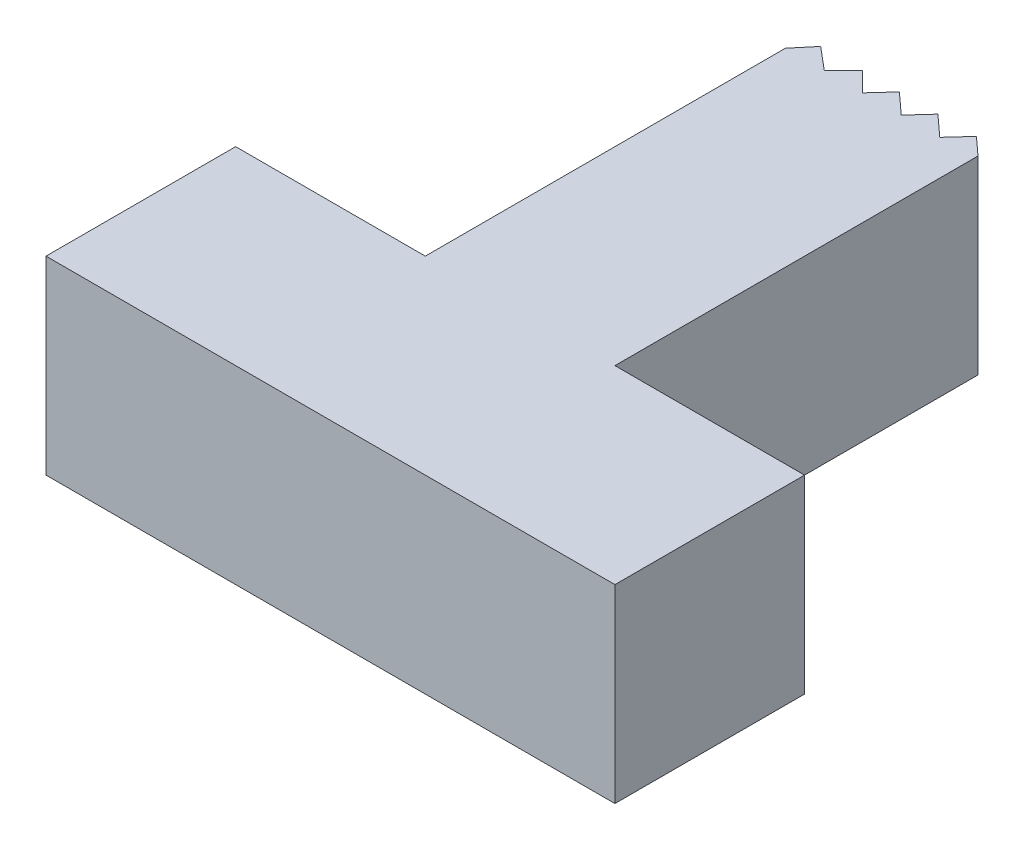
SolidWorks part; units mm, degrees
ref_plane "前视基准面" through (0, 0, 0) normal (0, 0, 1) x (1, 0, 0)
ref_plane "上视基准面" through (0, 0, 0) normal (0, 1, 0) x (1, 0, 0)
ref_plane "右视基准面" through (0, 0, 0) normal (1, 0, 0) x (0, 0, -1)
sketch "草图1" plane through (0, 0, 0) normal (0, 0, 1) x (1, 0, 0)
  line L1 (-3, 1) -> (3, 1)
  line L2 (-3, 1) -> (-3, -1)
  line L3 (-3, -1) -> (3, -1)
  line L4 (3, 1) -> (3, -1)
  line L5 (-3, 1) -> (3, -1) construction
  line L6 (-3, -1) -> (3, 1) construction
  point P0 (0, 0)
extrude "凸台-拉伸1" add sketch "草图1" along normal blind 2
sketch "草图2" plane through (0, 0, 0) normal (0, 0, -1) x (-1, 0, 0)
  line L0 (3, -1) -> (-3, -1) construction
  line L1 (-1, 1) -> (1, 1)
  line L2 (-1, 1) -> (-1, -1)
  line L3 (-1, -1) -> (1, -1)
  line L4 (1, 1) -> (1, -1)
  line L5 (-1, 1) -> (1, -1) construction
  line L6 (-1, -1) -> (1, 1) construction
  point P0 (0, 0)
extrude "凸台-拉伸2" add sketch "草图2" along normal blind 4
sketch "草图3" plane through (0, 1, 0) normal (0, 1, 0) x (1, 0, 0)
  line L0 (-1, 3.7977) -> (-0.8306, 4)
  line L1 (-1, 4) -> (-1, 0) construction
  line L2 (-1, 4) -> (1, 4) construction
  line L3 (-0.8306, 4) -> (-0.5891, 3.7977)
  line L4 (-0.5891, 3.7977) -> (-0.3877, 4)
  line L5 (-0.3877, 4) -> (-0.1845, 3.7977)
  line L6 (-0.1845, 3.7977) -> (0, 4)
  line L7 (0, 4) -> (0.2218, 3.7977)
  line L8 (0.2218, 3.7977) -> (0.4063, 4)
  line L9 (0.4063, 4) -> (0.6281, 3.7977)
  line L10 (0.6281, 3.7977) -> (0.8126, 4)
  line L11 (0.8126, 4) -> (1, 3.829)
  line L12 (1, 4) -> (1, 0) construction
  line L13 (1, 3.829) -> (1.1337, 3.829)
  line L14 (1.1337, 3.829) -> (1.1337, 4.1639)
  line L15 (1.1337, 4.1639) -> (-1.1016, 4.1639)
  line L16 (-1.1016, 4.1639) -> (-1.1016, 3.7977)
  line L17 (-1.1016, 3.7977) -> (-1, 3.7977)
extrude "切除-拉伸1" cut sketch "草图3" against normal blind 4
